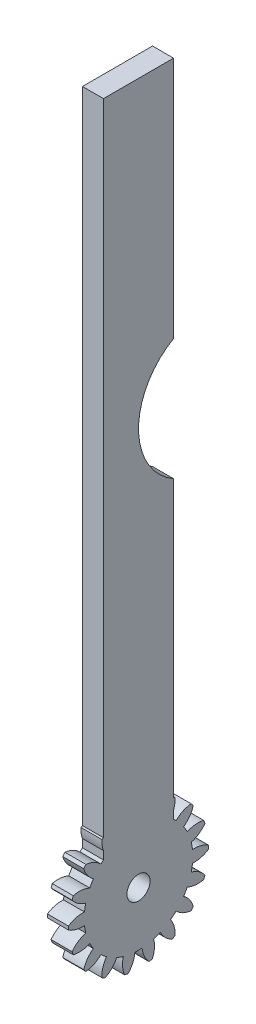
SolidWorks part; units mm, degrees
ref_plane "Plane1" through (0, 0, 0) normal (0, 0, 1) x (1, 0, 0)
ref_plane "Plane2" through (0, 0, 0) normal (0, 1, 0) x (1, 0, 0)
ref_plane "Plane3" through (0, 0, 0) normal (1, 0, 0) x (0, 0, -1)
sketch "HoldingSke" plane through (0, 0, 0) normal (0, 1, 0) x (1, 0, 0)
  line L0 (0, 0) -> (0.9511, -0.309)
  line L1 (-15, 0) -> (100, 0) construction
  line L2 (0, 0) -> (-2.1039, 2.3779)
  line L3 (0, 0) -> (-11.863, 4.5341)
  line L4 (0, 0) -> (8.2133, 2.6687)
  line L5 (0, 0) -> (-46.8476, -17.4728)
  line L6 (0, 0) -> (-2.4869, -1.6779)
  line L7 (-2.1039, 2.3779) -> (8.6586, 51.2059)
  line L8 (-76.2, 54.61) -> (-76.1, 54.61)
  line L9 (-71.009, 38.7566) -> (-53.1078, 45.2721)
  line L10 (-76.2, 71.12) -> (104.1128, 71.12)
  line L11 (0, 0) -> (-3, 0)
  line L12 (-76.2, 101.6) -> (-76.162, 101.6)
  line L13 (24.9733, 27.94) -> (52.9518, 28.4284)
  line L14 (24.9733, 27.94) -> (24.9743, 27.94)
  line L15 (24.9733, 27.94) -> (100.4006, 29.5858)
  line L16 (-63.627, -1) -> (-12.827, -1)
  circle A0 centre (0, 0) radius 0.5
  circle A1 centre (0, 0) radius 7.749
  circle A2 centre (0, 0) radius 37.5
  circle A3 centre (0, 0) radius 0.5
  dimension "MHD" = 15.498
  dimension "Hub_dia" = 75
  dimension "Bore" = 1
  dimension "MBD" = 1
  dimension "Num_teeth" = 18
  dimension "Pitch" = 1
  dimension "Overall_len" = 50
  dimension "Show_teeth" = 18
  dimension "Thickness" = 3
  dimension "OAL" = 50.0001
  dimension "T_dim" = 0.1
  dimension "Ap" = 20
  dimension "H" = 19.05
  dimension "Pitch_radius" = 180.3128
  dimension "Width" = 3
  dimension "Backlash" = 0.038
  dimension "Addendum_fac" = 1
  dimension "Dedendum_fac" = 1.25
  dimension "Clearance_fac" = 0.25
  dimension "Dedendum_add" = 0.001
  dimension "Module" = 1
sketch "BasProSke" plane through (0, 0, 0) normal (0, 1, 0) x (1, 0, 0)
  line L0 (-10, 0) -> (60, 0) construction
  line L1 (0, 0) -> (0, 10)
  line L2 (0, 0) -> (3, 0)
  line L3 (3, 0) -> (3, 10)
  line L4 (3, 10) -> (0, 10)
  dimension "Thickness" = 3
  dimension "Diameter" = 20
revolve "Base-Revolve" add sketch "BasProSke" angle 360 about L0
sketch "TooCutSke" plane through (0, 0, 0) normal (1, 0, 0) x (0, 0, -1)
  line L1 (0, 0) -> (0, 107) construction
  line L2 (0, 0) -> (-0.8509, 8.9597) construction
  line L3 (0, 0) -> (-3.1157, 17.6701) construction
  line L4 (-0.8509, 8.9597) -> (-1.5579, 8.835) construction
  arc A0 (0.5106, 7.7322) -> (-0.5106, 7.7322) centre (0, 0) ccw
  arc A1 (1.5152, 9.9102) -> (-1.5152, 9.9102) centre (0, 0) ccw
  circle A2 centre (0, 0) radius 9 construction
  circle A3 centre (0, 0) radius 8.4572 construction
  arc A4 (-0.5106, 7.7322) -> (-1.5152, 9.9102) centre (-4.0952, 7.3996) ccw
  arc A5 (1.5152, 9.9102) -> (0.5106, 7.7322) centre (4.0952, 7.3996) ccw
  dimension "Root_dia" = 15.498
  dimension "Overcut_dia" = 20.0508
  dimension "Pitch_dia" = 18
  dimension "Base_dia" = 16.9145
  dimension "Flank_rad" = 3.6
  dimension "Half_ang" = 10
  dimension "Half_CT" = 0.7179
extrude "ToothCut" cut sketch "TooCutSke" along normal through all
fillet "Breaks" [suppressed] radius 0.02
fillet "RootFillets" [suppressed] radius 0.251
pattern_circular "TeethCuts" count 18 every 20 about axis through (-10, 0, 0) along (1, 0, 0) of "ToothCut", "RootFillets", "Breaks"
sketch "HubNeaOneSke" plane through (0, 0, 0) normal (-1, 0, 0) x (0, 0, 1)
  circle A0 centre (0, 0) radius 7.749
  dimension "Diameter" = 15.498
extrude "HubNearOne" [suppressed] add sketch "HubNeaOneSke" along normal blind 47.0001
sketch "HubNeaBotSke" plane through (0, 0, 0) normal (-1, 0, 0) x (0, 0, 1)
  circle A0 centre (0, 0) radius 7.749
  dimension "Diameter" = 15.498
extrude "HubNearBoth" [suppressed] add sketch "HubNeaBotSke" along normal blind 23.5
ref_plane "FarPln" through (3, 0, 0) normal (1, 0, 0) x (0, 0, -1)
sketch "HubFarSke" plane through (3, 0, 0) normal (1, 0, 0) x (0, 0, -1)
  circle A0 centre (0, 0) radius 7.749
  dimension "Diameter" = 15.498
extrude "HubFar" [suppressed] add sketch "HubFarSke" along normal blind 23.5
sketch "BorSke" plane through (0, 0, 0) normal (1, 0, 0) x (0, 0, -1)
  circle A0 centre (0, 0) radius 0.5
  dimension "Diameter" = 1
extrude "Bore" cut sketch "BorSke" along normal mid plane 100.0001
sketch "KeySke" plane through (0, 0, 0) normal (1, 0, 0) x (0, 0, -1)
  line L0 (-0.05, 0) -> (-0.05, 0.6)
  line L1 (-0.05, 0.6) -> (0.05, 0.6)
  line L2 (0.05, 0.6) -> (0.05, 0)
  line L3 (0, 0) -> (0, 34) construction
  line L4 (-0.05, 0) -> (0.05, 0)
  dimension "Offset" = 0.6
  dimension "Width" = 0.1
extrude "Keyway" [suppressed] cut sketch "KeySke" along normal mid plane 100.0001
pattern_circular "Keyway2" [suppressed] count 2 every 90 about axis through (-10, 0, 0) along (1, 0, 0)
sketch "Sketch7" plane through (3, 0, 0) normal (1, 0, 0) x (0, 0, -1)
  line L0 (-5, 0) -> (-5, 100)
  line L1 (-5, 100) -> (5, 100)
  line L2 (5, 100) -> (5, 0)
  line L3 (5, 0) -> (-5, 0)
  dimension "D1" = 10
extrude "Boss-Extrude5" add sketch "Sketch7" against normal blind 3
sketch "Sketch10" plane through (3, 0, 0) normal (1, 0, 0) x (0, 0, -1)
  line L0 (10, 66.6927) -> (10, 46.6927)
  line L1 (5, 8.6603) -> (5, 100) construction
  arc A0 (10, 66.6927) -> (10, 46.6927) centre (10, 56.6927) ccw
  dimension "D1" = 5
extrude "Cut-Extrude1" cut sketch "Sketch10" against normal blind 3 contours A0 L0
sketch "Sketch11" plane through (0, 0, 0) normal (-1, 0, 0) x (0, 0, 1)
  line L0 (0.5, 0) -> (-0.5, 0) construction
  circle A0 centre (0, 0) radius 1.65
extrude "Cut-Extrude2" cut sketch "Sketch11" against normal blind 3
equation "' \"Module@HoldingSke\" = 6.35"
equation "' \"Num_teeth@HoldingSke\" = 12"
equation "' \"Ap@HoldingSke\" =  20"
equation "' \"Ap@HoldingSke\" = 20"
equation "' \"Width@HoldingSke\" = 0.5 * 25.4"
equation "' \"Hub_dia@HoldingSke\"= 1 * 25.4"
equation "' \"Hub_dia@HoldingSke\" = 1 * 25.4"
equation "' \"Overall_len@HoldingSke\" = 1.0 * 25.4"
equation "' \"Bore@HoldingSke\" = 0.75 * 25.4"
equation "' \"T_dim@HoldingSke\" = 0.1 * 25.4"
equation "' \"Width@KeySke\" = 0.25 * 25.4"
equation "' \"Show_teeth@HoldingSke\" = 13"
equation "' \"Backlash@HoldingSke\" = 0.009 * 25.4"
equation "' \"Addendum_fac@HoldingSke\" = 1.0"
equation "' \"Dedendum_fac@HoldingSke\" = 1.25"
equation "' \"Dedendum_add@HoldingSke\" = 0.00005 * 25.4"
equation "' \"Clearance_fac@HoldingSke\" = 0.25"
equation "\"Pitch@HoldingSke\" = 1 / \"Module@HoldingSke\""
equation "\"Overcut_dia@TooCutSke\" = (\"Num_teeth@HoldingSke\" + 2 * \"Addendum_fac@HoldingSke\") / \"Pitch@HoldingSke\" + 0.002 * 25.4"
equation "\"Pitch_dia@TooCutSke\" = \"Num_teeth@HoldingSke\" / \"Pitch@HoldingSke\""
equation "\"Base_dia@TooCutSke\" = \"Num_teeth@HoldingSke\" / \"Pitch@HoldingSke\" * cos((\"Ap@HoldingSke\"  * 3.14159265 / 180))"
equation "\"Root_dia@TooCutSke\" = (\"Num_teeth@HoldingSke\" + 2) / \"Pitch@HoldingSke\" - 2 * (\"Addendum_fac@HoldingSke\" + \"Dedendum_fac@HoldingSke\") / \"Pitch@HoldingSke\" - \"Dedendum_add@HoldingSke\" * 2"
equation "\"Half_ang@TooCutSke\" = 180 / \"Num_teeth@HoldingSke\""
equation "\"Half_CT@TooCutSke\" = \"Num_teeth@HoldingSke\" / \"Pitch@HoldingSke\" * sin((3.14159265 / 2 / \"Num_teeth@HoldingSke\")) / 2 - 7 * \"Backlash@HoldingSke\" / 4"
equation "\"Flank_rad@TooCutSke\" = \"Num_teeth@HoldingSke\" / \"Pitch@HoldingSke\" / 5"
equation "\"Radius@RootFillets\" = \"Clearance_fac@HoldingSke\" / \"Pitch@HoldingSke\" + \"Dedendum_add@HoldingSke\""
equation "\"Break_rad@Breaks\" = 0.02 / \"Pitch@HoldingSke\""
equation "\"Thickness@HoldingSke\" = \"Width@HoldingSke\""
equation "\"OAL@HoldingSke\" = \"Thickness@HoldingSke\""
equation "\"MHD@HoldingSke\" = (\"Num_teeth@HoldingSke\" + 2) / \"Pitch@HoldingSke\" - 2 * (\"Addendum_fac@HoldingSke\" + \"Dedendum_fac@HoldingSke\")  / \"Pitch@HoldingSke\" - \"Dedendum_add@HoldingSke\" * 2"
equation "\"MBD@HoldingSke\" = (\"Num_teeth@HoldingSke\" + 2) / \"Pitch@HoldingSke\" - 2 * (\"Addendum_fac@HoldingSke\" + \"Dedendum_fac@HoldingSke\")  / \"Pitch@HoldingSke\" - \"Dedendum_add@HoldingSke\" * 2 - 0.002 * 25.4"
equation "\"MHD@HoldingSke\" = ((sgn( \"MHD@HoldingSke\" - \"Hub_dia@HoldingSke\" )-1)*( \"MHD@HoldingSke\" - \"Hub_dia@HoldingSke\" ))/-2+ \"Hub_dia@HoldingSke\""
equation "\"MBD@HoldingSke\" = ((sgn( \"MBD@HoldingSke\" - \"Bore@HoldingSke\" )-1)*( \"MBD@HoldingSke\" - \"Bore@HoldingSke\" ))/-2+ \"Bore@HoldingSke\""
equation "\"OAL@HoldingSke\" = ((sgn( \"OAL@HoldingSke\" - \"Overall_len@HoldingSke\" )+1)*( \"OAL@HoldingSke\" - \"Overall_len@HoldingSke\" ))/2 + \"Overall_len@HoldingSke\" + 0.000002 * 25.4"
equation "\"Num_teeth@TeethCuts\" = int( \"Show_teeth@HoldingSke\" ) + 1"
equation "\"Num_teeth@TeethCuts\" = ((sgn( \"Num_teeth@TeethCuts\" - \"Num_teeth@HoldingSke\" )-1)*( \"Num_teeth@TeethCuts\" - \"Num_teeth@HoldingSke\" ))/-2+ \"Num_teeth@HoldingSke\""
equation "\"Num_teeth@TeethCuts\" = ((sgn( \"Num_teeth@TeethCuts\" - 2.0)+1)*( \"Num_teeth@TeethCuts\" - 2.0))/2 +2.0"
equation "\"Angle@TeethCuts\" = 360.0 / \"Num_teeth@HoldingSke\""
equation "\"Diameter@BasProSke\" = (\"Num_teeth@HoldingSke\" + 2 * \"Addendum_fac@HoldingSke\") / \"Pitch@HoldingSke\""
equation "\"Thickness@BasProSke\"  = \"Thickness@HoldingSke\""
equation "' \"Fillet_rad@BasProSke\" =  \"Thickness@HoldingSke\" * 0.05"
equation "' \"Fillet_rad@BasProSke\" = \"Thickness@HoldingSke\" * 0.05"
equation "\"MHD@HoldingSke\" = ((sgn( \"MHD@HoldingSke\" - \"Root_dia@TooCutSke\" )-1)*( \"MHD@HoldingSke\" - \"Root_dia@TooCutSke\" ))/-2+ \"Root_dia@TooCutSke\""
equation "\"Diameter@HubNeaOneSke\" = \"MHD@HoldingSke\""
equation "\"Length@HubNearOne\" = \"OAL@HoldingSke\" - \"Thickness@BasProSke\""
equation "\"Diameter@HubNeaBotSke\" = \"MHD@HoldingSke\""
equation "\"Length@HubNearBoth\" = ( \"OAL@HoldingSke\" - \"Thickness@BasProSke\" ) / 2.0"
equation "\"Thickness@FarPln\" = \"Thickness@BasProSke\""
equation "\"Diameter@HubFarSke\" = \"MHD@HoldingSke\""
equation "\"Length@HubFar\" = ( \"OAL@HoldingSke\" - \"Thickness@BasProSke\" ) / 2.0"
equation "\"Diameter@BorSke\" = \"MBD@HoldingSke\""
equation "\"D1@Bore\" = \"OAL@HoldingSke\" * 2.0"
equation "\"D1@Keyway\" = \"OAL@HoldingSke\" * 2.0"
equation "\"Offset@KeySke\" = \"T_dim@HoldingSke\" + \"MBD@HoldingSke\" / 2.0"
